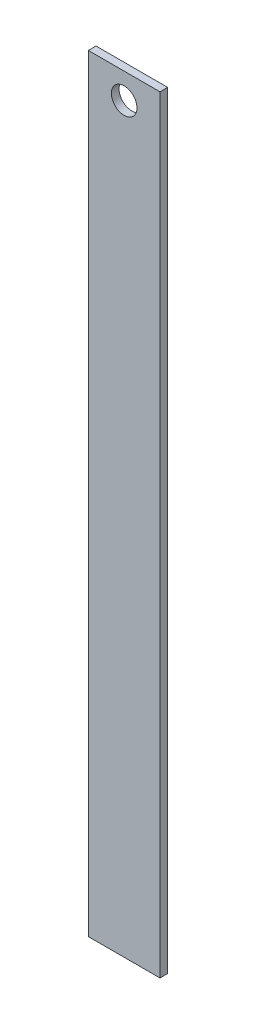
SolidWorks part; units mm, degrees
material "7075-T6 (SN)"
ref_plane "Alzado" through (0, 0, 0) normal (0, 0, 1) x (1, 0, 0)
ref_plane "Planta" through (0, 0, 0) normal (0, 1, 0) x (1, 0, 0)
ref_plane "Vista lateral" through (0, 0, 0) normal (1, 0, 0) x (0, 0, -1)
sketch "Croquis1" plane through (0, 0, 0) normal (0, 0, 1) x (1, 0, 0)
  line L1 (14, -150) -> (-14, -150)
  line L2 (14, -150) -> (14, 150)
  line L3 (14, 150) -> (-14, 150)
  line L4 (-14, -150) -> (-14, 150)
  line L5 (14, -150) -> (-14, 150) construction
  line L6 (14, 150) -> (-14, -150) construction
  point P0 (0, 0)
  dimension "D1" = 300
  dimension "D2" = 28
extrude "Saliente-Extruir1" add sketch "Croquis1" along normal blind 3
sketch "Croquis2" plane through (0, 0, 0) normal (0, 0, -1) x (-1, 0, 0)
  line L0 (0, 150) -> (0, 140) construction
  line L1 (-14, 150) -> (14, 150) construction
  circle A0 centre (0, 140) radius 5
  dimension "D1" = 10
  dimension "D2" = 10
extrude "Cortar-Extruir1" cut sketch "Croquis2" against normal through all
